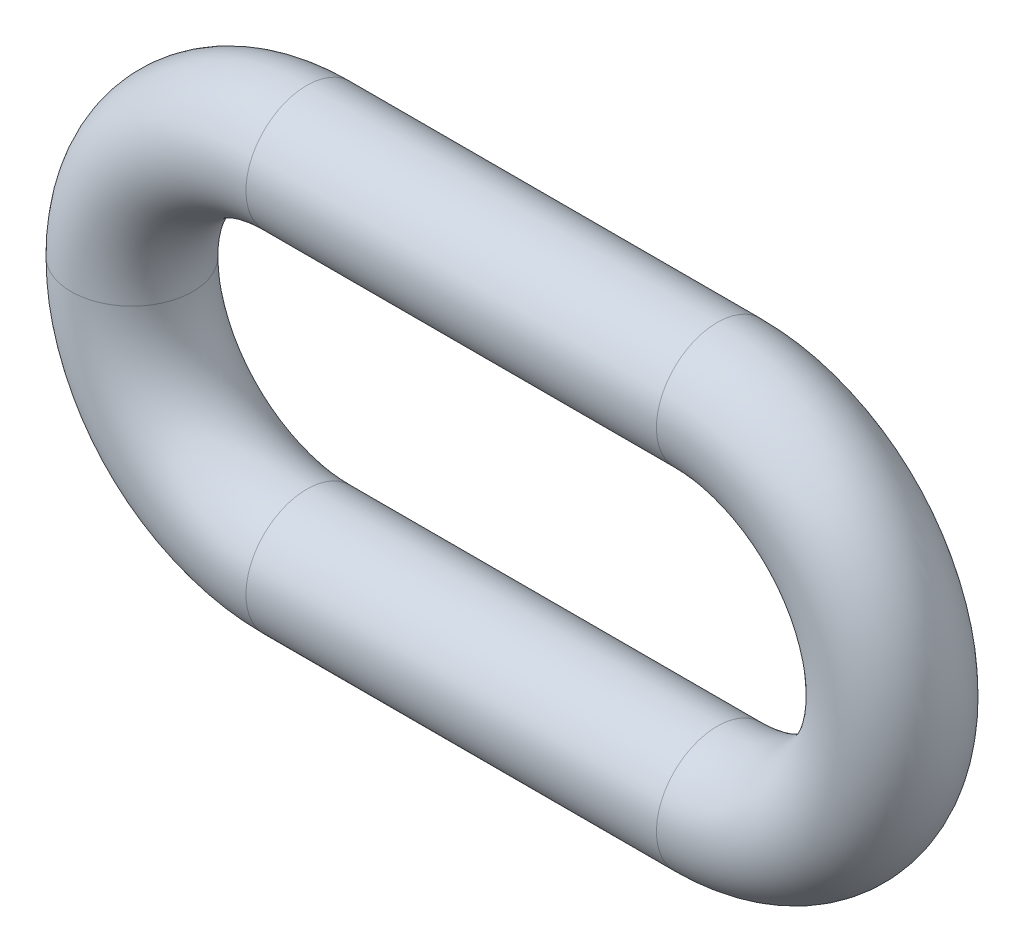
SolidWorks part; units mm, degrees
material "AISI 304"
ref_plane "Спереди" through (0, 0, 0) normal (0, 0, 1) x (1, 0, 0)
ref_plane "Сверху" through (0, 0, 0) normal (0, 1, 0) x (1, 0, 0)
ref_plane "Справа" through (0, 0, 0) normal (1, 0, 0) x (0, 0, -1)
sketch "Эскиз1" plane through (0, 0, 0) normal (0, 0, 1) x (1, 0, 0)
  line L0 (19.25, 0) -> (5.75, 0) construction
  line L1 (19.25, -5.75) -> (5.75, -5.75)
  line L2 (19.25, 5.75) -> (5.75, 5.75)
  arc A0 (19.25, -5.75) -> (19.25, 5.75) centre (19.25, 0) ccw
  arc A1 (5.75, 5.75) -> (5.75, -5.75) centre (5.75, 0) ccw
  point P3 (12.5, 0)
  dimension "D1" = 11.5
  dimension "D2" = 13.5
sketch "Эскиз2" plane through (0, 0, 0) normal (0, 1, 0) x (1, 0, 0)
  circle A0 centre (0, 0) radius 2
  dimension "D1" = 4
sweep "По траектории1" add profiles "Эскиз2" path "Эскиз1"
sketch "Эскиз3" plane through (0, 0, 0) normal (0, 0, 1) x (1, 0, 0)
  line L0 (2, 0) -> (21, 0) construction
  line L1 (12.5, 7.75) -> (12.5, -7.75) construction
  line L2 (19.25, 7.75) -> (5.75, 7.75) construction
  line L3 (5.75, -7.75) -> (19.25, -7.75) construction
  line L4 (21, 0) -> (27, 0) construction
  arc A2 (19.25, -7.75) -> (19.25, 7.75) centre (19.25, 0) ccw construction
  arc A5 (19.25, -3.75) -> (19.25, 3.75) centre (19.25, 0) ccw construction
  point P4 (23, 0)
  dimension "D1" = 15.5
  dimension "19" = 19
  dimension "D3" = 2
ref_point "Точка2"
ref_point "Точка4"
ref_point "Точка5"
